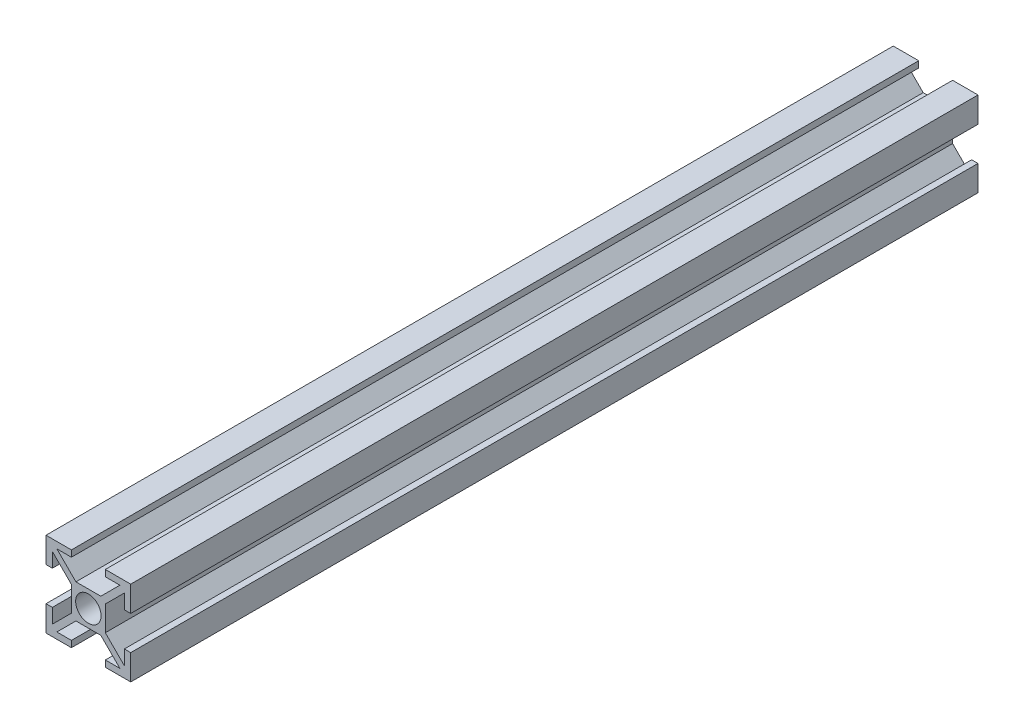
SolidWorks part; units mm, degrees
ref_plane "Plano frontal" through (0, 0, 0) normal (0, 0, 1) x (1, 0, 0)
ref_plane "Plano superior" through (0, 0, 0) normal (0, 1, 0) x (1, 0, 0)
ref_plane "Plano direito" through (0, 0, 0) normal (1, 0, 0) x (0, 0, -1)
sketch "Esboço1" plane through (0, 0, 0) normal (0, 0, 1) x (1, 0, 0)
  line L0 (-2.9393, 4) -> (2.9393, 4)
  line L1 (-10, -10) -> (-4, -10)
  line L2 (-10, -10) -> (-10, -4)
  line L3 (-10, 10) -> (-4, 10)
  line L4 (10, -10) -> (10, -4)
  line L5 (-10, -10) -> (-4, -4) construction
  line L6 (-10, 10) -> (-4, 4) construction
  line L7 (-7.4393, -8.5) -> (-2.9393, -4)
  line L8 (4, -10) -> (10, -10)
  line L9 (-8.5, -7.4393) -> (-4, -2.9393)
  line L10 (-8.5, 7.4393) -> (-4, 2.9393)
  line L11 (-7.4393, -8.5) -> (-4, -8.5)
  line L12 (-8.5, -7.4393) -> (-8.5, -4)
  line L13 (-7.4393, 8.5) -> (-4, 8.5)
  line L14 (8.5, -7.4393) -> (8.5, -4)
  line L15 (-8.5, -8.5) -> (-4, -4) construction
  line L16 (-8.5, 8.5) -> (-4, 4) construction
  line L17 (-4, 10) -> (-4, 8.5)
  line L18 (4, -8.5) -> (7.4393, -8.5)
  line L19 (-10, -4) -> (-8.5, -4)
  line L20 (4, 10) -> (4, 8.5)
  line L21 (-10, 4) -> (-8.5, 4)
  line L22 (-4, 2.9393) -> (-4, -2.9393)
  line L23 (-4, -8.5) -> (-4, -10)
  line L24 (-8.5, 4) -> (-8.5, 7.4393)
  line L25 (-10, 4) -> (-10, 10)
  line L26 (-7.4393, 8.5) -> (-2.9393, 4)
  line L27 (4, 8.5) -> (7.4393, 8.5)
  line L28 (-2.9393, -4) -> (2.9393, -4)
  line L29 (4, 10) -> (10, 10)
  line L30 (4, -8.5) -> (4, -10)
  line L31 (10, 4) -> (10, 10)
  line L32 (8.5, 4) -> (8.5, 7.4393)
  line L33 (-10.5303, -9.4697) -> (9.4697, 10.5303) construction
  line L34 (8.5, 4) -> (10, 4)
  line L35 (8.5, -4) -> (10, -4)
  line L36 (-10, -10) -> (10, 10) construction
  line L37 (4, 2.9393) -> (4, -2.9393)
  line L38 (-9.4697, -10.5303) -> (10.5303, 9.4697) construction
  line L40 (2.9393, -4) -> (7.4393, -8.5)
  line L41 (4, -4) -> (10, -10) construction
  line L42 (4, -4) -> (8.5, -8.5) construction
  line L43 (4, -2.9393) -> (8.5, -7.4393)
  line L44 (4, 0) -> (10, 0) construction
  line L45 (4, 2.9393) -> (8.5, 7.4393)
  line L46 (4, 4) -> (8.5, 8.5) construction
  line L47 (4, 4) -> (10, 10) construction
  line L48 (2.9393, 4) -> (7.4393, 8.5)
  circle A0 centre (0, 0) radius 3
  point P0 (0, 0)
  point P14 (0, 0)
  dimension "D1" = 0.75
  dimension "D3" = 1.5
  dimension "D4" = 20
  dimension "D2" = 0.75
extrude "Ressalto-extrusão1" add sketch "Esboço1" along normal blind 200
